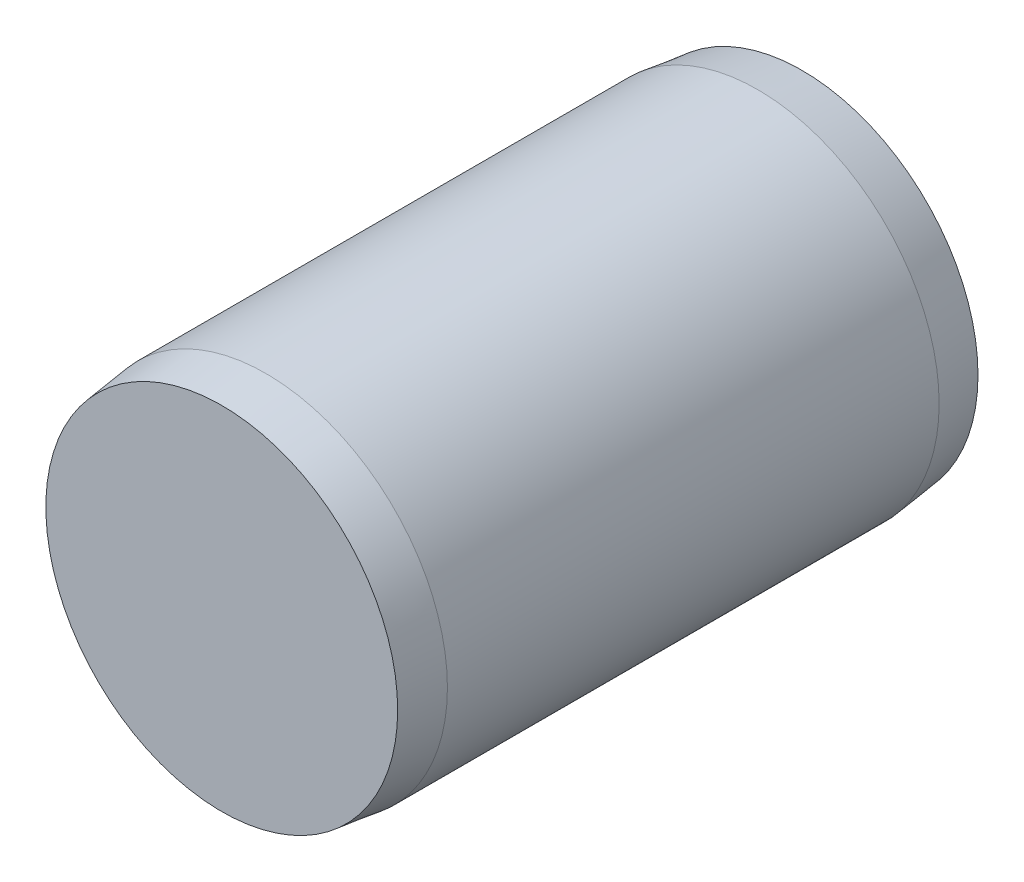
SolidWorks part; units mm, degrees
ref_plane "Front Plane" through (0, 0, 0) normal (0, 0, 1) x (1, 0, 0)
ref_plane "Top Plane" through (0, 0, 0) normal (0, 1, 0) x (1, 0, 0)
ref_plane "Right Plane" through (0, 0, 0) normal (1, 0, 0) x (0, 0, -1)
sketch "Sketch1" plane through (0, 0, 0) normal (0, 1, 0) x (1, 0, 0)
  line L0 (2.425, 8) -> (0, 8)
  line L1 (0, 8) -> (0, 0)
  line L2 (0, 0) -> (2.425, 0)
  line L3 (2.425, 0) -> (2.5, 0.6108)
  line L4 (2.5, 0.6108) -> (2.5, 7.3892)
  line L5 (2.5, 7.3892) -> (2.425, 8)
  line L6 (0, 8) -> (0, 0) construction
revolve "Revolve1" add sketch "Sketch1" angle 360 about L6
